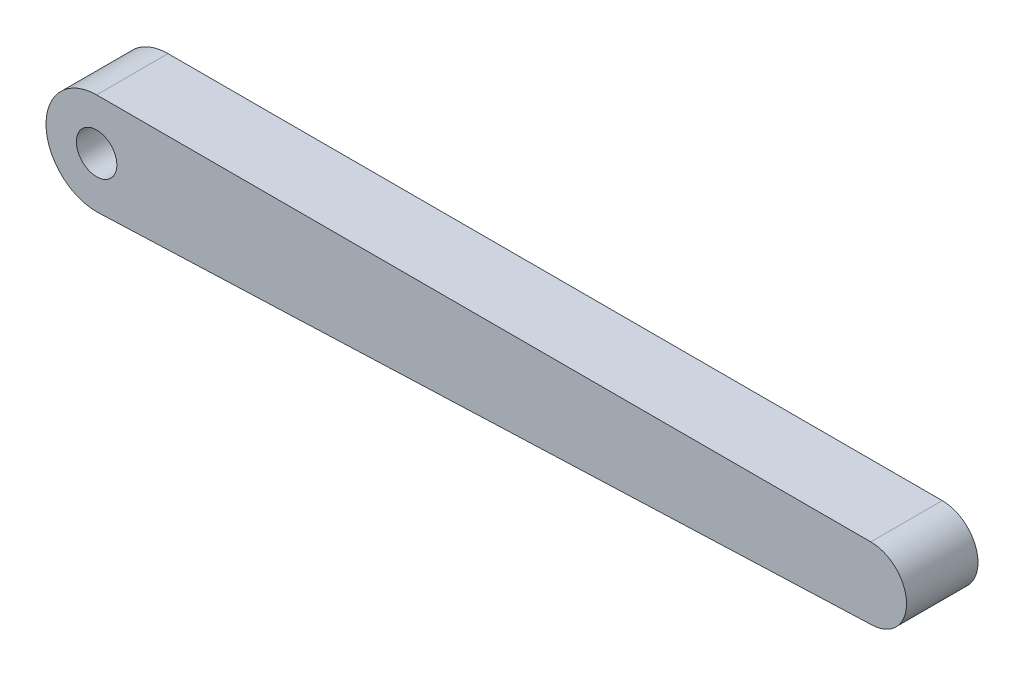
SolidWorks part; units mm, degrees
ref_plane "前视基准面" through (0, 0, 0) normal (0, 0, 1) x (1, 0, 0)
ref_plane "上视基准面" through (0, 0, 0) normal (0, 1, 0) x (1, 0, 0)
ref_plane "右视基准面" through (0, 0, 0) normal (1, 0, 0) x (0, 0, -1)
other "Configuration Table"
sketch "草图2" plane through (0, 0, 0) normal (0, 0, 1) x (1, 0, 0)
  line L0 (0, 0) -> (65, 0)
  line L2 (65, -6) -> (0, -8.5)
  arc A0 (0, 0) -> (0, -8.5) centre (0, -4.25) ccw
  arc A1 (65, 0) -> (65, -6) centre (65, -3) cw
  dimension "D1" = 8.5
  dimension "D2" = 6
  dimension "D3" = 65
extrude "凸台-拉伸1" add sketch "草图2" along normal blind 6
sketch "草图3" plane through (0, 0, 6) normal (0, 0, 1) x (1, 0, 0)
  circle A0 centre (0, -4.25) radius 1.7
  dimension "D1" = 3.4
extrude "切除-拉伸1" cut sketch "草图3" against normal blind 3.5
